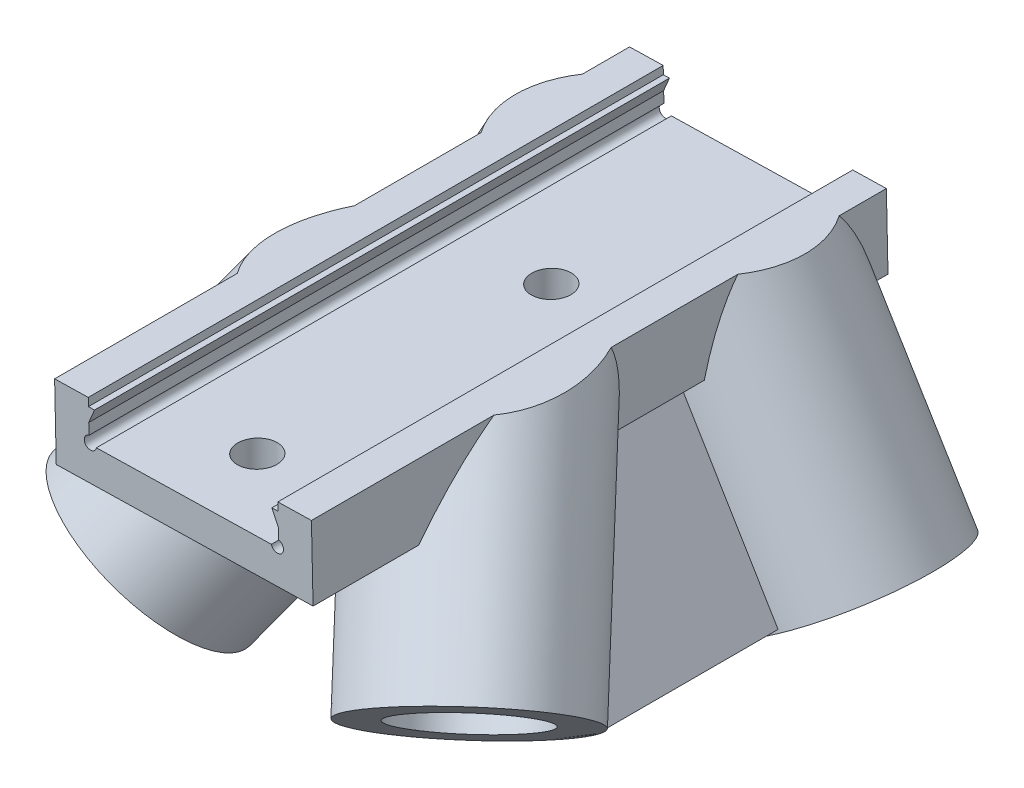
SolidWorks part; units mm, degrees
ref_plane "Top Plane" through (0, 0, 0) normal (0, 0, 1) x (1, 0, 0)
ref_plane "Front Plane" through (0, 0, 0) normal (0, 1, 0) x (1, 0, 0)
ref_plane "Right Plane" through (0, 0, 0) normal (1, 0, 0) x (0, 0, -1)
sketch3d "3DSketch1"
  line L0 (0, 0, 0) -> (-20.8036, -37.9764, 25)
  line L1 (0, 0, 0) -> (0, 0, 50)
  line L2 (0, 0, 0) -> (22.4868, -37.0047, 25)
  line L4 (0, 0, 0) -> (0.9982, -44.4695, 0) construction
  line L5 (22.4868, -37.0047, 25) -> (0, 0, 25) construction
  line L6 (0, 0, 25) -> (-20.8036, -37.9764, 25) construction
  line L7 (0, 0, 25) -> (1.5979, -71.1844, 25) construction
  line L8 (0, 0, 0) -> (0, 0, -14)
  line L9 (0, 0, -14) -> (-20.1749, -36.8287, -14)
  line L10 (0, 0, -14) -> (21.8071, -35.8863, -14)
  line L11 (0, 0, -14) -> (0.9902, -44.1111, -14) construction
  dimension "D1" = 30
  dimension "D7" = 14
  dimension "D2" = 60
  dimension "D3" = 60
  dimension "D4" = 50
  dimension "D5" = 30
  dimension "D6" = 90
  dimension "D8" = 30
  dimension "D9" = 30
ref_plane "Plane5" through (0, 0, 0) normal (0, 0, 1) x (1, 0, 0)
ref_plane "Plane2" through (0, 0, 0) normal (0, 0, 1) x (-0.9679, 0.2514, 0)
sketch "Sketch3" plane through (0, 0, 0) normal (0, 0, 1) x (-0.9679, 0.2514, 0)
  line L0 (-7.2341, -12.968) -> (12.968, -7.2341)
  line L1 (-7.2341, -12.968) -> (-12.968, 7.2341)
  line L2 (12.968, -7.2341) -> (7.2341, 12.968)
  line L3 (-12.968, 7.2341) -> (7.2341, 12.968)
  line L4 (12.968, -7.2341) -> (-12.968, 7.2341) construction
  line L5 (-7.2341, -12.968) -> (7.2341, 12.968) construction
  line L6 (0, 0) -> (-12.145, 42.7905) construction
  point P0 (0, 0)
  dimension "D1" = 21
extrude "Boss-Extrude1" add sketch "Sketch3" along normal blind 25 and the other way blind 22 contours L0 L2 L3 L1
ref_plane "Plane3" through (0, 0, 0) normal (0.4497, -0.7401, 0.5) x (-0.7399, -0.6223, -0.2556)
sketch "Sketch5" plane through (0, 0, 0) normal (0.4497, -0.7401, 0.5) x (-0.7399, -0.6223, -0.2556)
  circle A0 centre (0, 0) radius 8
  dimension "D1" = 16
extrude "Boss-Extrude2" add sketch "Sketch5" along normal blind 30
ref_plane "Plane4" through (0, 0, 0) normal (-0.4161, -0.7595, 0.5) x (-0.7036, 0.6172, 0.3522)
sketch "Sketch6" plane through (0, 0, 0) normal (-0.4161, -0.7595, 0.5) x (-0.7036, 0.6172, 0.3522)
  circle A0 centre (0, 0) radius 8
  dimension "D1" = 16
extrude "Boss-Extrude3" add sketch "Sketch6" along normal blind 30
ref_plane "Plane6" through (0, 0, -14) normal (-0.4804, -0.877, 0) x (-0.877, 0.4804, 0)
sketch "Sketch18" plane through (0, 0, -14) normal (-0.4804, -0.877, 0) x (-0.877, 0.4804, 0)
  circle A0 centre (0, 0) radius 8
  dimension "D1" = 16
extrude "Boss-Extrude4" add sketch "Sketch18" along normal blind 30
ref_plane "Plane7" through (0, 0, -14) normal (0.5193, -0.8546, 0) x (-0.8546, -0.5193, 0)
sketch "Sketch19" plane through (0, 0, -14) normal (0.5193, -0.8546, 0) x (-0.8546, -0.5193, 0)
  circle A0 centre (0, 0) radius 8
  dimension "D1" = 16
extrude "Boss-Extrude5" add sketch "Sketch19" along normal blind 30
sketch "Sketch11" plane through (0, 0, 25) normal (0, 0, 1) x (0.9679, -0.2514, 0)
  line L0 (-9.5716, 5.3395) -> (9.5716, -5.3395) construction
  line L1 (5.3395, 9.5716) -> (-5.3395, -9.5716) construction
  line L8 (9.5716, -5.3395) -> (5.3395, 9.5716)
  line L9 (5.3395, 9.5716) -> (-9.5716, 5.3395)
  line L10 (-9.5716, 5.3395) -> (-5.3395, -9.5716)
  line L11 (-5.3395, -9.5716) -> (9.5716, -5.3395)
  line L12 (9.5716, -5.3395) -> (5.3395, 9.5716)
  line L13 (5.3395, 9.5716) -> (-9.5716, 5.3395)
  line L14 (-9.5716, 5.3395) -> (-5.3395, -9.5716)
  line L15 (-5.3395, -9.5716) -> (9.5716, -5.3395)
  circle A0 centre (9.4406, -5.2664) radius 0.5
  circle A1 centre (-5.2664, -9.4406) radius 0.5
  dimension "D2" = 0.15
  dimension "D3" = 0.15
  dimension "D4" = 1
  dimension "D1" = 2.75
extrude "Cut-Extrude4" cut sketch "Sketch11" against normal through all contours L14 A1 L15 | L15 A0 L12 | A1 L15 A0 L12 L13 L14
sketch "Sketch12" plane through (0.2356, -10.4974, 0) normal (-0.0224, 0.9997, 0) x (0.0743, 0.0017, -0.9972)
  line L0 (-24.9309, -1.8576) -> (-17.3519, -1.2929) construction
  line L1 (-18.9475, -1.4118) -> (5.0192, 0.374) construction
  line L2 (-24.1507, -12.3285) -> (-25.7111, 8.6134) construction
  circle A0 centre (-18.9475, -1.4118) radius 1.6
  circle A1 centre (5.0192, 0.374) radius 1.6
  dimension "D1" = 3.2
  dimension "D2" = 6
extrude "Cut-Extrude5" cut sketch "Sketch12" along normal up to next
sketch "Sketch14" plane through (0, 0, 25) normal (0, 0, 1) x (1, 0, 0)
  line L0 (-31.1058, -5.1994) -> (38.3527, -3.6402)
  line L1 (10.733, -10.2617) -> (-10.2617, -10.733) construction
  line L2 (38.3527, -3.6402) -> (37.9887, 12.5741)
  line L3 (37.9887, 12.5741) -> (-33.7452, 10.9639)
  line L4 (-33.7452, 10.9639) -> (-31.1058, -5.1994)
  dimension "D1" = 6
extrude "TopCut" cut sketch "Sketch14" against normal through all
sketch "Sketch17" plane through (0, 0, 25) normal (0, 0, -1) x (-1, 0, 0)
  line L0 (7.6075, -6.4338) -> (7.1326, -5.3114)
  line L2 (7.1326, -5.3114) -> (7.6325, -5.3226)
  line L4 (-0.2356, -10.4974) -> (-0.1739, -7.748) construction
  line L6 (-7.3638, -4.986) -> (-7.8636, -4.9748)
  line L7 (-7.8886, -6.086) -> (-7.3638, -4.986)
  line L8 (7.6075, -6.4338) -> (7.6325, -5.3226)
  line L9 (-7.8886, -6.086) -> (-7.8636, -4.9748)
  line L10 (7.6471, -4.6728) -> (7.5875, -7.3274) construction
  line L11 (6.9796, -7.9086) -> (-7.3274, -7.5875) construction
  line L12 (-10.733, -10.2617) -> (10.2617, -10.733) construction
  line M37 (-7.849, -4.3249) -> (-7.9086, -6.9796)
  line M41 (7.5875, -7.3274) -> (7.6471, -4.6728)
  dimension "D1" = 2.6
  dimension "D2" = 0.5
  dimension "D3" = 1.4885
extrude "GrabTabs" add sketch "Sketch17" along normal through all contours L0 L2 M41 | L7 L6 M37
sketch "Sketch20" plane through (13.4921, -22.2028, 15) normal (0.4497, -0.7401, 0.5) x (-0.8932, -0.3727, 0.2518)
  circle A0 centre (0, 0) radius 5.1
  dimension "D1" = 10.2
sketch "Sketch21" plane through (15.5793, -25.6376, 0) normal (0.5193, -0.8546, 0) x (0.8546, 0.5193, 0)
  circle A0 centre (0, -14) radius 5.1
  dimension "D1" = 10.2
sketch "Sketch22" plane through (-14.4132, -26.3109, 0) normal (-0.4804, -0.877, 0) x (0.877, -0.4804, 0)
  circle A0 centre (0, -14) radius 5.1
  dimension "D1" = 10.2
sketch "Sketch23" plane through (-12.4822, -22.7859, 15) normal (-0.4161, -0.7595, 0.5) x (0.9093, -0.3475, 0.2288)
  circle A0 centre (0, 0) radius 5.1
  dimension "D1" = 10.2
sketch "Sketch24" plane through (0, 0, -22) normal (0, 0, -1) x (-1, 0, 0)
  line L0 (-13.8181, -26.3982) -> (-17.4097, -24.2383)
  line L1 (-13.8181, -26.3982) -> (-4.3179, -10.6001)
  line L2 (-17.4097, -24.2383) -> (-7.9095, -8.4403)
  line L3 (-4.3179, -10.6001) -> (-7.9095, -8.4403)
  line L4 (-0.2356, -10.4974) -> (-0.1739, -7.748) construction
  line L5 (-6.2963, -10.3613) -> (5.825, -10.6334) construction
  line L6 (6.9796, -7.9086) -> (-7.3274, -7.5875) construction
  line L7 (3.8379, -10.7832) -> (7.5228, -8.7867)
  line L8 (12.6196, -26.9916) -> (16.3045, -24.9952)
  line L9 (16.3045, -24.9952) -> (7.5228, -8.7867)
  line L10 (12.6196, -26.9916) -> (3.8379, -10.7832)
extrude "Boss-Extrude6" add sketch "Sketch24" along direction (0, 0, 1) on the side against the normal blind 30.5
extrude "Cut-Extrude6" cut sketch "Sketch22" against normal blind 14 contours A0
extrude "Cut-Extrude7" cut sketch "Sketch23" against normal blind 14
extrude "Cut-Extrude8" cut sketch "Sketch20" against normal blind 14 contours A0
extrude "Cut-Extrude9" cut sketch "Sketch21" against normal blind 14 contours A0
